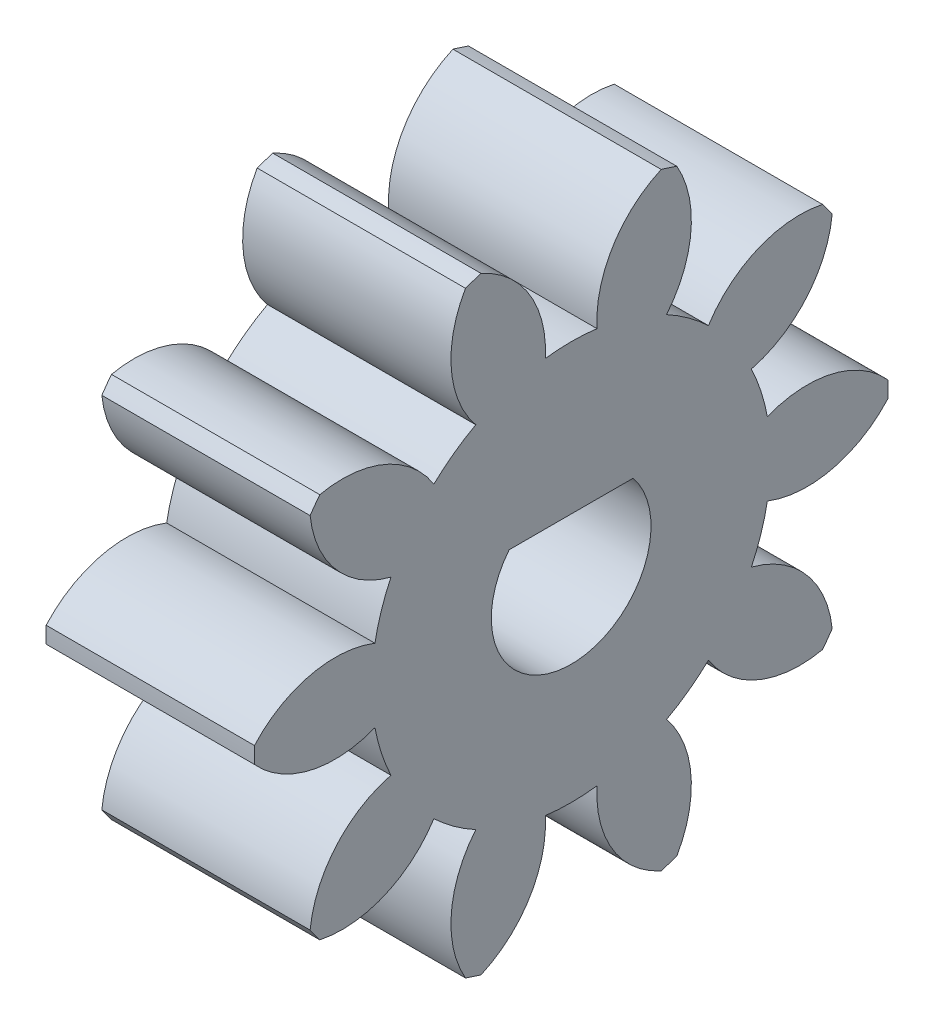
SolidWorks part; units mm, degrees
ref_plane "Plane1" through (0, 0, 0) normal (0, 0, 1) x (1, 0, 0)
ref_plane "Plane2" through (0, 0, 0) normal (0, 1, 0) x (1, 0, 0)
ref_plane "Plane3" through (0, 0, 0) normal (1, 0, 0) x (0, 0, -1)
sketch "HoldingSke" plane through (0, 0, 0) normal (0, 1, 0) x (1, 0, 0)
  line L0 (0, 0) -> (0.6565, -0.1158)
  line L1 (-15, 0) -> (100, 0) construction
  line L2 (0, 0) -> (-2.1039, 2.3779)
  line L3 (0, 0) -> (-11.863, 4.5341)
  line L4 (0, 0) -> (8.5048, 1.4996)
  line L5 (0, 0) -> (-46.8476, -17.4728)
  line L6 (0, 0) -> (-4.9738, -3.3558)
  line L7 (-2.1039, 2.3779) -> (8.6586, 51.2059)
  line L8 (-76.2, 54.61) -> (-75.3, 54.61)
  line L9 (-71.009, 38.7566) -> (-53.1078, 45.2721)
  line L10 (-76.2, 71.12) -> (104.1128, 71.12)
  line L11 (0, 0) -> (-6, 0)
  line L12 (-76.2, 101.6) -> (-76.147, 101.6)
  line L13 (24.9733, 27.94) -> (52.9518, 28.4284)
  line L14 (24.9733, 27.94) -> (24.9743, 27.94)
  line L15 (24.9733, 27.94) -> (100.4006, 29.5858)
  line L16 (-63.627, -1.5) -> (-12.827, -1.5)
  circle A0 centre (0, 0) radius 2.5
  circle A1 centre (0, 0) radius 5.624
  circle A2 centre (0, 0) radius 37.5
  circle A3 centre (0, 0) radius 2.5
  dimension "MHD" = 11.248
  dimension "Hub_dia" = 75
  dimension "Bore" = 5
  dimension "MBD" = 5
  dimension "Num_teeth" = 10
  dimension "Pitch_radius" = 180.3128
  dimension "Pitch" = 0.6667
  dimension "Width" = 6
  dimension "Overall_len" = 50
  dimension "Show_teeth" = 10
  dimension "Thickness" = 6
  dimension "OAL" = 50.0001
  dimension "T_dim" = 0.9
  dimension "Ap" = 20
  dimension "H" = 19.05
  dimension "Backlash" = 0.053
  dimension "Addendum_fac" = 1
  dimension "Dedendum_fac" = 1.25
  dimension "Clearance_fac" = 0.25
  dimension "Dedendum_add" = 0.001
  dimension "Module" = 1.5
sketch "BasProSke" plane through (0, 0, 0) normal (0, 1, 0) x (1, 0, 0)
  line L0 (-10, 0) -> (60, 0) construction
  line L1 (0, 0) -> (0, 9)
  line L2 (0, 0) -> (6, 0)
  line L3 (6, 0) -> (6, 9)
  line L4 (6, 9) -> (0, 9)
  dimension "Diameter" = 18
  dimension "Thickness" = 6
revolve "Base-Revolve" add sketch "BasProSke" angle 360 about L0
sketch "TooCutSke" plane through (0, 0, 0) normal (1, 0, 0) x (0, 0, -1)
  line L1 (0, 0) -> (0, 107) construction
  line L2 (0, 0) -> (-1.2658, 7.3924) construction
  line L3 (0, 0) -> (-4.5869, 14.117) construction
  line L4 (-1.2658, 7.3924) -> (-2.2934, 7.0585) construction
  arc A0 (0.8839, 5.5541) -> (-0.8839, 5.5541) centre (0, 0) ccw
  arc A1 (2.6378, 8.6313) -> (-2.6378, 8.6313) centre (0, 0) ccw
  circle A2 centre (0, 0) radius 7.5 construction
  circle A3 centre (0, 0) radius 7.0477 construction
  arc A4 (-0.8839, 5.5541) -> (-2.6378, 8.6313) centre (-3.8646, 5.8936) ccw
  arc A5 (2.6378, 8.6313) -> (0.8839, 5.5541) centre (3.8646, 5.8936) ccw
  dimension "Root_dia" = 11.248
  dimension "Overcut_dia" = 18.0508
  dimension "Pitch_dia" = 15
  dimension "Base_dia" = 14.0954
  dimension "Flank_rad" = 3
  dimension "Half_ang" = 18
  dimension "Half_CT" = 1.0805
extrude "ToothCut" cut sketch "TooCutSke" along normal through all
fillet "Breaks" [suppressed] radius 0.03
fillet "RootFillets" [suppressed] radius 0.376
pattern_circular "TeethCuts" count 10 every 36 about axis through (-10, 0, 0) along (1, 0, 0) of "ToothCut", "RootFillets", "Breaks"
sketch "HubNeaOneSke" plane through (0, 0, 0) normal (-1, 0, 0) x (0, 0, 1)
  circle A0 centre (0, 0) radius 5.624
  dimension "Diameter" = 11.248
extrude "HubNearOne" [suppressed] add sketch "HubNeaOneSke" along normal blind 44.0001
sketch "HubNeaBotSke" plane through (0, 0, 0) normal (-1, 0, 0) x (0, 0, 1)
  circle A0 centre (0, 0) radius 5.624
  dimension "Diameter" = 11.248
extrude "HubNearBoth" [suppressed] add sketch "HubNeaBotSke" along normal blind 22
ref_plane "FarPln" through (6, 0, 0) normal (1, 0, 0) x (0, 0, -1)
sketch "HubFarSke" plane through (6, 0, 0) normal (1, 0, 0) x (0, 0, -1)
  circle A0 centre (0, 0) radius 5.624
  dimension "Diameter" = 11.248
extrude "HubFar" [suppressed] add sketch "HubFarSke" along normal blind 22
sketch "BorSke" plane through (0, 0, 0) normal (1, 0, 0) x (0, 0, -1)
  circle A0 centre (0, 0) radius 2.5
  dimension "Diameter" = 5
extrude "Bore" cut sketch "BorSke" along normal mid plane 100.0001
sketch "KeySke" plane through (0, 0, 0) normal (1, 0, 0) x (0, 0, -1)
  line L0 (-1, 0) -> (-1, 3.4)
  line L1 (-1, 3.4) -> (1, 3.4)
  line L2 (1, 3.4) -> (1, 0)
  line L3 (0, 0) -> (0, 34) construction
  line L4 (-1, 0) -> (1, 0)
  dimension "Offset" = 3.4
  dimension "Width" = 2
extrude "Keyway" [suppressed] cut sketch "KeySke" along normal mid plane 100.0001
pattern_circular "Keyway2" [suppressed] count 2 every 90 about axis through (-10, 0, 0) along (1, 0, 0)
sketch "Sketch1" plane through (0, 0, 0) normal (-1, 0, 0) x (0, 0, 1)
  line L0 (50, 0) -> (-50, 0) construction
  line L1 (-1.7854, 1.45) -> (1.7854, 1.45)
  arc A41 (-1.7854, 1.45) -> (1.7854, 1.45) centre (0, 0) ccw
  arc A80 (-3.9538, 4.1735) -> (-7.2407, 5.5531) centre (-6.5907, 2.4965) ccw
  arc A81 (-7.2407, 5.5531) -> (-7.5189, 5.1703) centre (0, 0) ccw
  arc A82 (-7.5189, 5.1703) -> (-5.1911, 2.4706) centre (-4.4109, 5.4967) ccw
  arc A83 (-5.1911, 2.4706) -> (-5.6518, 1.0524) centre (0, 0) ccw
  arc A84 (-5.6518, 1.0524) -> (-9.1219, 0.2366) centre (-6.7994, -1.8542) ccw
  arc A85 (-9.1219, 0.2366) -> (-9.1219, -0.2366) centre (0, 0) ccw
  arc A86 (-9.1219, -0.2366) -> (-5.6518, -1.0524) centre (-6.7994, 1.8542) ccw
  arc A87 (-5.6518, -1.0524) -> (-5.1911, -2.4706) centre (0, 0) ccw
  arc A88 (-5.1911, -2.4706) -> (-7.5189, -5.1703) centre (-4.4109, -5.4967) ccw
  arc A89 (-7.5189, -5.1703) -> (-7.2407, -5.5531) centre (0, 0) ccw
  arc A90 (-7.2407, -5.5531) -> (-3.9538, -4.1735) centre (-6.5907, -2.4965) ccw
  arc A91 (-3.9538, -4.1735) -> (-2.7475, -5.05) centre (0, 0) ccw
  arc A92 (-2.7475, -5.05) -> (-3.0438, -8.6024) centre (-0.3377, -7.0396) ccw
  arc A93 (-3.0438, -8.6024) -> (-2.5938, -8.7486) centre (0, 0) ccw
  arc A94 (-2.5938, -8.7486) -> (-0.7456, -5.7004) centre (-3.8646, -5.8936) ccw
  arc A95 (-0.7456, -5.7004) -> (0.7456, -5.7004) centre (0, 0) ccw
  arc A96 (0.7456, -5.7004) -> (2.5938, -8.7486) centre (3.8646, -5.8936) ccw
  arc A97 (2.5938, -8.7486) -> (3.0438, -8.6024) centre (0, 0) ccw
  arc A98 (3.0438, -8.6024) -> (2.7475, -5.05) centre (0.3377, -7.0396) ccw
  arc A99 (2.7475, -5.05) -> (3.9538, -4.1735) centre (0, 0) ccw
  arc A100 (3.9538, -4.1735) -> (7.2407, -5.5531) centre (6.5907, -2.4965) ccw
  arc A101 (7.2407, -5.5531) -> (7.5189, -5.1703) centre (0, 0) ccw
  arc A102 (7.5189, -5.1703) -> (5.1911, -2.4706) centre (4.4109, -5.4967) ccw
  arc A103 (5.1911, -2.4706) -> (5.6518, -1.0524) centre (0, 0) ccw
  arc A104 (5.6518, -1.0524) -> (9.1219, -0.2366) centre (6.7994, 1.8542) ccw
  arc A105 (9.1219, -0.2366) -> (9.1219, 0.2366) centre (0, 0) ccw
  arc A106 (9.1219, 0.2366) -> (5.6518, 1.0524) centre (6.7994, -1.8542) ccw
  arc A107 (5.6518, 1.0524) -> (5.1911, 2.4706) centre (0, 0) ccw
  arc A108 (5.1911, 2.4706) -> (7.5189, 5.1703) centre (4.4109, 5.4967) ccw
  arc A109 (7.5189, 5.1703) -> (7.2407, 5.5531) centre (0, 0) ccw
  arc A110 (7.2407, 5.5531) -> (3.9538, 4.1735) centre (6.5907, 2.4965) ccw
  arc A111 (3.9538, 4.1735) -> (2.7475, 5.05) centre (0, 0) ccw
  arc A112 (2.7475, 5.05) -> (3.0438, 8.6024) centre (0.3377, 7.0396) ccw
  arc A113 (3.0438, 8.6024) -> (2.5938, 8.7486) centre (0, 0) ccw
  arc A114 (2.5938, 8.7486) -> (0.7456, 5.7004) centre (3.8646, 5.8936) ccw
  arc A115 (0.7456, 5.7004) -> (-0.7456, 5.7004) centre (0, 0) ccw
  arc A116 (-0.7456, 5.7004) -> (-2.5938, 8.7486) centre (-3.8646, 5.8936) ccw
  arc A117 (-2.5938, 8.7486) -> (-3.0438, 8.6024) centre (0, 0) ccw
  arc A118 (-3.0438, 8.6024) -> (-2.7475, 5.05) centre (-0.3377, 7.0396) ccw
  arc A119 (-2.7475, 5.05) -> (-3.9538, 4.1735) centre (0, 0) ccw
  arc A120 (-3.9538, 4.1735) -> (-7.2407, 5.5531) centre (-6.5907, 2.4965) ccw
  arc A121 (-7.2407, 5.5531) -> (-7.5189, 5.1703) centre (0, 0) ccw
  arc A122 (-7.5189, 5.1703) -> (-5.1911, 2.4706) centre (-4.4109, 5.4967) ccw
  arc A123 (-5.1911, 2.4706) -> (-5.6518, 1.0524) centre (0, 0) ccw
  arc A124 (-5.6518, 1.0524) -> (-9.1219, 0.2366) centre (-6.7994, -1.8542) ccw
  arc A125 (-9.1219, 0.2366) -> (-9.1219, -0.2366) centre (0, 0) ccw
  arc A126 (-9.1219, -0.2366) -> (-5.6518, -1.0524) centre (-6.7994, 1.8542) ccw
  arc A127 (-5.6518, -1.0524) -> (-5.1911, -2.4706) centre (0, 0) ccw
  arc A128 (-5.1911, -2.4706) -> (-7.5189, -5.1703) centre (-4.4109, -5.4967) ccw
  arc A129 (-7.5189, -5.1703) -> (-7.2407, -5.5531) centre (0, 0) ccw
  arc A130 (-7.2407, -5.5531) -> (-3.9538, -4.1735) centre (-6.5907, -2.4965) ccw
  arc A131 (-3.9538, -4.1735) -> (-2.7475, -5.05) centre (0, 0) ccw
  arc A132 (-2.7475, -5.05) -> (-3.0438, -8.6024) centre (-0.3377, -7.0396) ccw
  arc A133 (-3.0438, -8.6024) -> (-2.5938, -8.7486) centre (0, 0) ccw
  arc A134 (-2.5938, -8.7486) -> (-0.7456, -5.7004) centre (-3.8646, -5.8936) ccw
  arc A135 (-0.7456, -5.7004) -> (0.7456, -5.7004) centre (0, 0) ccw
  arc A136 (0.7456, -5.7004) -> (2.5938, -8.7486) centre (3.8646, -5.8936) ccw
  arc A137 (2.5938, -8.7486) -> (3.0438, -8.6024) centre (0, 0) ccw
  arc A138 (3.0438, -8.6024) -> (2.7475, -5.05) centre (0.3377, -7.0396) ccw
  arc A139 (2.7475, -5.05) -> (3.9538, -4.1735) centre (0, 0) ccw
  arc A140 (3.9538, -4.1735) -> (7.2407, -5.5531) centre (6.5907, -2.4965) ccw
  arc A141 (7.2407, -5.5531) -> (7.5189, -5.1703) centre (0, 0) ccw
  arc A142 (7.5189, -5.1703) -> (5.1911, -2.4706) centre (4.4109, -5.4967) ccw
  arc A143 (5.1911, -2.4706) -> (5.6518, -1.0524) centre (0, 0) ccw
  arc A144 (5.6518, -1.0524) -> (9.1219, -0.2366) centre (6.7994, 1.8542) ccw
  arc A145 (9.1219, -0.2366) -> (9.1219, 0.2366) centre (0, 0) ccw
  arc A146 (9.1219, 0.2366) -> (5.6518, 1.0524) centre (6.7994, -1.8542) ccw
  arc A147 (5.6518, 1.0524) -> (5.1911, 2.4706) centre (0, 0) ccw
  arc A148 (5.1911, 2.4706) -> (7.5189, 5.1703) centre (4.4109, 5.4967) ccw
  arc A149 (7.5189, 5.1703) -> (7.2407, 5.5531) centre (0, 0) ccw
  arc A150 (7.2407, 5.5531) -> (3.9538, 4.1735) centre (6.5907, 2.4965) ccw
  arc A151 (3.9538, 4.1735) -> (2.7475, 5.05) centre (0, 0) ccw
  arc A152 (2.7475, 5.05) -> (3.0438, 8.6024) centre (0.3377, 7.0396) ccw
  arc A153 (3.0438, 8.6024) -> (2.5938, 8.7486) centre (0, 0) ccw
  arc A154 (2.5938, 8.7486) -> (0.7456, 5.7004) centre (3.8646, 5.8936) ccw
  arc A155 (0.7456, 5.7004) -> (-0.7456, 5.7004) centre (0, 0) ccw
  arc A156 (-0.7456, 5.7004) -> (-2.5938, 8.7486) centre (-3.8646, 5.8936) ccw
  arc A157 (-2.5938, 8.7486) -> (-3.0438, 8.6024) centre (0, 0) ccw
  arc A158 (-3.0438, 8.6024) -> (-2.7475, 5.05) centre (-0.3377, 7.0396) ccw
  arc A159 (-2.7475, 5.05) -> (-3.9538, 4.1735) centre (0, 0) ccw
  dimension "D3" = 1.45
  dimension "D4" = 3.5707
  dimension "D1" = 0.125
extrude "Boss-Extrude2" add sketch "Sketch1" against normal up to surface (6 mm away) up to face at (6, 0, 0)
equation "' \"Module@HoldingSke\" = 6.35"
equation "' \"Num_teeth@HoldingSke\" = 12"
equation "' \"Ap@HoldingSke\" =  20"
equation "' \"Width@HoldingSke\" = 0.5 * 25.4"
equation "' \"Hub_dia@HoldingSke\"= 1 * 25.4"
equation "' \"Overall_len@HoldingSke\" = 1.0 * 25.4"
equation "' \"Bore@HoldingSke\" = 0.75 * 25.4"
equation "' \"T_dim@HoldingSke\" = 0.1 * 25.4"
equation "' \"Width@KeySke\" = 0.25 * 25.4"
equation "' \"Show_teeth@HoldingSke\" = 13"
equation "' \"Backlash@HoldingSke\" = 0.009 * 25.4"
equation "' \"Addendum_fac@HoldingSke\" = 1.0"
equation "' \"Dedendum_fac@HoldingSke\" = 1.25"
equation "' \"Dedendum_add@HoldingSke\" = 0.00005 * 25.4"
equation "' \"Clearance_fac@HoldingSke\" = 0.25"
equation "\"Pitch@HoldingSke\" = 1 / \"Module@HoldingSke\""
equation "\"Overcut_dia@TooCutSke\" = (\"Num_teeth@HoldingSke\" + 2 * \"Addendum_fac@HoldingSke\") / \"Pitch@HoldingSke\" + 0.002 * 25.4"
equation "\"Pitch_dia@TooCutSke\" = \"Num_teeth@HoldingSke\" / \"Pitch@HoldingSke\""
equation "\"Base_dia@TooCutSke\" = \"Num_teeth@HoldingSke\" / \"Pitch@HoldingSke\" * cos((\"Ap@HoldingSke\"  * 3.14159265 / 180))"
equation "\"Root_dia@TooCutSke\" = (\"Num_teeth@HoldingSke\" + 2) / \"Pitch@HoldingSke\" - 2 * (\"Addendum_fac@HoldingSke\" + \"Dedendum_fac@HoldingSke\") / \"Pitch@HoldingSke\" - \"Dedendum_add@HoldingSke\" * 2"
equation "\"Half_ang@TooCutSke\" = 180 / \"Num_teeth@HoldingSke\""
equation "\"Half_CT@TooCutSke\" = \"Num_teeth@HoldingSke\" / \"Pitch@HoldingSke\" * sin((3.14159265 / 2 / \"Num_teeth@HoldingSke\")) / 2 - 7 * \"Backlash@HoldingSke\" / 4"
equation "\"Flank_rad@TooCutSke\" = \"Num_teeth@HoldingSke\" / \"Pitch@HoldingSke\" / 5"
equation "\"Radius@RootFillets\" = \"Clearance_fac@HoldingSke\" / \"Pitch@HoldingSke\" + \"Dedendum_add@HoldingSke\""
equation "\"Break_rad@Breaks\" = 0.02 / \"Pitch@HoldingSke\""
equation "\"Thickness@HoldingSke\" = \"Width@HoldingSke\""
equation "\"OAL@HoldingSke\" = \"Thickness@HoldingSke\""
equation "\"MHD@HoldingSke\" = (\"Num_teeth@HoldingSke\" + 2) / \"Pitch@HoldingSke\" - 2 * (\"Addendum_fac@HoldingSke\" + \"Dedendum_fac@HoldingSke\")  / \"Pitch@HoldingSke\" - \"Dedendum_add@HoldingSke\" * 2"
equation "\"MBD@HoldingSke\" = (\"Num_teeth@HoldingSke\" + 2) / \"Pitch@HoldingSke\" - 2 * (\"Addendum_fac@HoldingSke\" + \"Dedendum_fac@HoldingSke\")  / \"Pitch@HoldingSke\" - \"Dedendum_add@HoldingSke\" * 2 - 0.002 * 25.4"
equation "\"MHD@HoldingSke\" = ((sgn( \"MHD@HoldingSke\" - \"Hub_dia@HoldingSke\" )-1)*( \"MHD@HoldingSke\" - \"Hub_dia@HoldingSke\" ))/-2+ \"Hub_dia@HoldingSke\""
equation "\"MBD@HoldingSke\" = ((sgn( \"MBD@HoldingSke\" - \"Bore@HoldingSke\" )-1)*( \"MBD@HoldingSke\" - \"Bore@HoldingSke\" ))/-2+ \"Bore@HoldingSke\""
equation "\"OAL@HoldingSke\" = ((sgn( \"OAL@HoldingSke\" - \"Overall_len@HoldingSke\" )+1)*( \"OAL@HoldingSke\" - \"Overall_len@HoldingSke\" ))/2 + \"Overall_len@HoldingSke\" + 0.000002 * 25.4"
equation "\"Num_teeth@TeethCuts\" = int( \"Show_teeth@HoldingSke\" ) + 1"
equation "\"Num_teeth@TeethCuts\" = ((sgn( \"Num_teeth@TeethCuts\" - \"Num_teeth@HoldingSke\" )-1)*( \"Num_teeth@TeethCuts\" - \"Num_teeth@HoldingSke\" ))/-2+ \"Num_teeth@HoldingSke\""
equation "\"Num_teeth@TeethCuts\" = ((sgn( \"Num_teeth@TeethCuts\" - 2.0)+1)*( \"Num_teeth@TeethCuts\" - 2.0))/2 +2.0"
equation "\"Angle@TeethCuts\" = 360.0 / \"Num_teeth@HoldingSke\""
equation "\"Diameter@BasProSke\" = (\"Num_teeth@HoldingSke\" + 2 * \"Addendum_fac@HoldingSke\") / \"Pitch@HoldingSke\""
equation "\"Thickness@BasProSke\"  = \"Thickness@HoldingSke\""
equation "' \"Fillet_rad@BasProSke\" =  \"Thickness@HoldingSke\" * 0.05"
equation "\"MHD@HoldingSke\" = ((sgn( \"MHD@HoldingSke\" - \"Root_dia@TooCutSke\" )-1)*( \"MHD@HoldingSke\" - \"Root_dia@TooCutSke\" ))/-2+ \"Root_dia@TooCutSke\""
equation "\"Diameter@HubNeaOneSke\" = \"MHD@HoldingSke\""
equation "\"Length@HubNearOne\" = \"OAL@HoldingSke\" - \"Thickness@BasProSke\""
equation "\"Diameter@HubNeaBotSke\" = \"MHD@HoldingSke\""
equation "\"Length@HubNearBoth\" = ( \"OAL@HoldingSke\" - \"Thickness@BasProSke\" ) / 2.0"
equation "\"Thickness@FarPln\" = \"Thickness@BasProSke\""
equation "\"Diameter@HubFarSke\" = \"MHD@HoldingSke\""
equation "\"Length@HubFar\" = ( \"OAL@HoldingSke\" - \"Thickness@BasProSke\" ) / 2.0"
equation "\"Diameter@BorSke\" = \"MBD@HoldingSke\""
equation "\"D1@Bore\" = \"OAL@HoldingSke\" * 2.0"
equation "\"D1@Keyway\" = \"OAL@HoldingSke\" * 2.0"
equation "\"Offset@KeySke\" = \"T_dim@HoldingSke\" + \"MBD@HoldingSke\" / 2.0"
